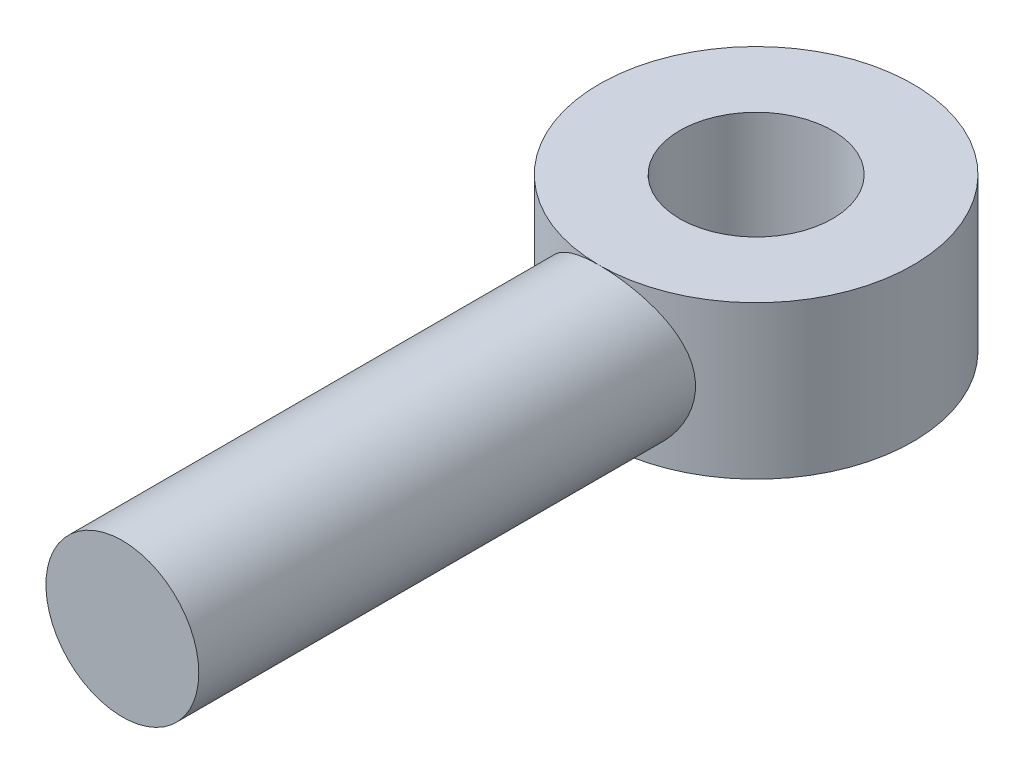
SolidWorks part; units mm, degrees
ref_plane "Front Plane" through (0, 0, 0) normal (0, 0, 1) x (1, 0, 0)
ref_plane "Top Plane" through (0, 0, 0) normal (0, 1, 0) x (1, 0, 0)
ref_plane "Right Plane" through (0, 0, 0) normal (1, 0, 0) x (0, 0, -1)
sketch "Sketch1" plane through (0, 0, 0) normal (0, 0, 1) x (1, 0, 0)
  circle A0 centre (0, 0) radius 20
  dimension "D1" = 40
extrude "Boss-Extrude1" add sketch "Sketch1" along normal blind 130
sketch "Sketch2" plane through (0, 0, 0) normal (0, 1, 0) x (1, 0, 0)
  line L0 (0, 0) -> (0, 71.7161) construction
  circle A0 centre (0, 35.8581) radius 41.0585
  point P5 (0, 0)
  point P6 (0, 0)
extrude "Boss-Extrude2" add sketch "Sketch2" along normal mid plane 40
sketch "Sketch8" plane through (0, 20, 0) normal (0, 1, 0) x (1, 0, 0)
  circle A0 centre (0, 35.8581) radius 20
  dimension "D1" = 40
sketch "Sketch10" plane through (0, 20, 0) normal (0, 1, 0) x (1, 0, 0)
extrude "Cut-Extrude1" cut sketch "Sketch8" against normal blind 40 contours A0
sketch "Sketch15" plane through (0, 20, 0) normal (0, 1, 0) x (1, 0, 0)
